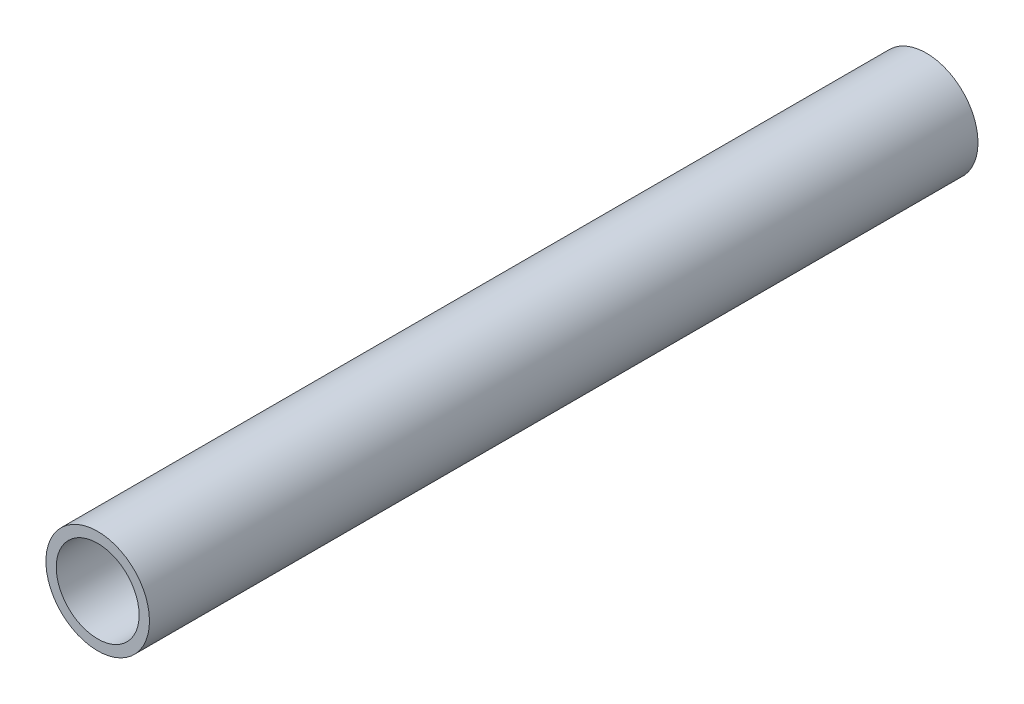
SolidWorks part; units mm, degrees
ref_plane "Plan de face" through (0, 0, 0) normal (0, 0, 1) x (1, 0, 0)
ref_plane "Plan de dessus" through (0, 0, 0) normal (0, 1, 0) x (1, 0, 0)
ref_plane "Plan de droite" through (0, 0, 0) normal (1, 0, 0) x (0, 0, -1)
sketch "Esquisse1" plane through (0, 0, 0) normal (0, 0, 1) x (1, 0, 0)
  circle A0 centre (0, 0) radius 10
  circle A1 centre (0, 0) radius 8
  dimension "D1" = 20
  dimension "D2" = 2
extrude "Boss.-Extru.1" add sketch "Esquisse1" along normal blind 160
